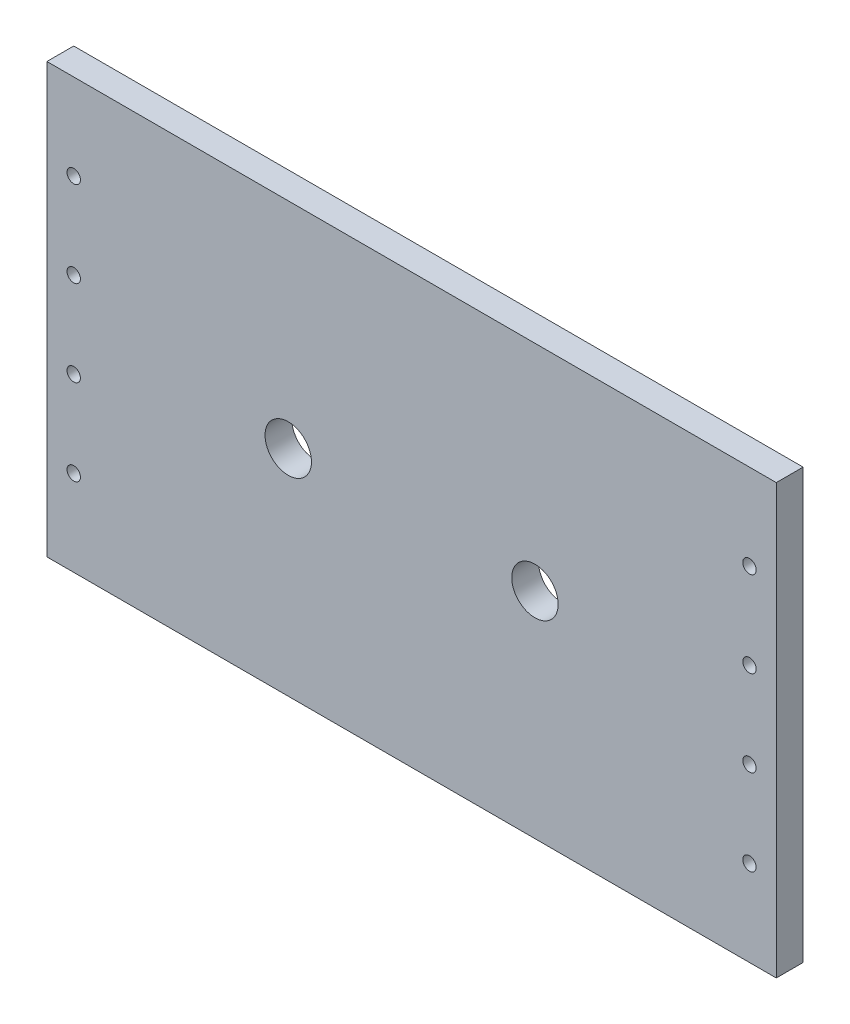
SolidWorks part; units mm, degrees
material "ABS"
ref_plane "Front Plane" through (0, 0, 0) normal (0, 0, 1) x (1, 0, 0)
ref_plane "Top Plane" through (0, 0, 0) normal (0, 1, 0) x (1, 0, 0)
ref_plane "Right Plane" through (0, 0, 0) normal (1, 0, 0) x (0, 0, -1)
sketch "Sketch1" plane through (0, 0, 0) normal (0, 0, 1) x (1, 0, 0)
  line L1 (0, 0) -> (172.72, 0)
  line L2 (0, 0) -> (0, 101.6)
  line L3 (0, 101.6) -> (172.72, 101.6)
  line L4 (172.72, 0) -> (172.72, 101.6)
  dimension "D1" = 101.6
  dimension "D2" = 172.72
extrude "Boss-Extrude1" add sketch "Sketch1" along normal blind 6.35
sketch "Sketch2" plane through (0, 0, 6.35) normal (0, 0, 1) x (1, 0, 0)
  line L0 (0, 0) -> (172.72, 0) construction
  line L1 (172.72, 101.6) -> (0, 101.6) construction
  line L3 (0, 101.6) -> (0, 0) construction
  line L4 (172.72, 0) -> (172.72, 101.6) construction
  circle A0 centre (6.35, 81.28) radius 1.5875
  circle A1 centre (6.35, 60.96) radius 1.5875
  circle A2 centre (6.35, 40.64) radius 1.5875
  circle A3 centre (6.35, 20.32) radius 1.5875
  circle A4 centre (166.37, 20.32) radius 1.5875
  circle A5 centre (166.37, 40.64) radius 1.5875
  circle A6 centre (166.37, 60.96) radius 1.5875
  circle A7 centre (166.37, 81.28) radius 1.5875
  dimension "D1" = 3.175
  dimension "D2" = 20.32
  dimension "D3" = 20.32
  dimension "D4" = 20.32
  dimension "D5" = 20.32
  dimension "D6" = 6.35
  dimension "D7" = 6.35
extrude "Cut-Extrude1" cut sketch "Sketch2" against normal blind 6.35
sketch "Sketch5" plane through (0, 0, 6.35) normal (0, 0, 1) x (1, 0, 0)
  line L0 (172.72, 101.6) -> (0, 101.6) construction
  line L13 (0, 101.6) -> (0, 0) construction
  circle A0 centre (115.57, 50.8) radius 5.4993
  circle A2 centre (57.15, 50.8) radius 5.4993
  dimension "D1" = 10.9985
  dimension "D2" = 50.8
  dimension "D3" = 57.15
  dimension "D4" = 58.42
extrude "Cut-Extrude3" cut sketch "Sketch5" against normal blind 6.35
